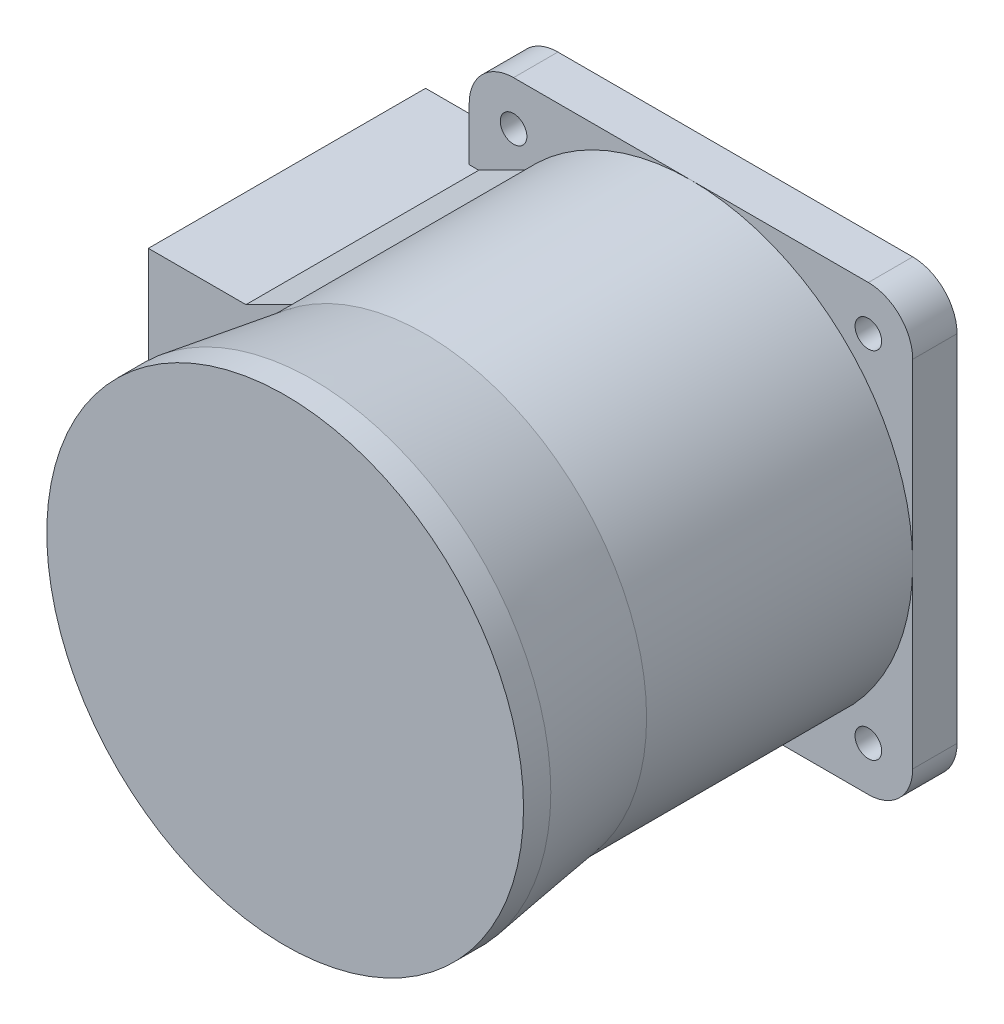
SolidWorks part; units mm, degrees
ref_plane "Piano frontale" through (0, 0, 0) normal (0, 0, 1) x (1, 0, 0)
ref_plane "Piano superiore" through (0, 0, 0) normal (0, 1, 0) x (1, 0, 0)
ref_plane "Piano destro" through (0, 0, 0) normal (1, 0, 0) x (0, 0, -1)
sketch "Schizzo1" plane through (0, 0, 0) normal (0, 0, 1) x (1, 0, 0)
  line L0 (0, 100) -> (0, -100) construction
  line L1 (-80, -100) -> (80, -100)
  line L2 (-100, -80) -> (-100, 80)
  line L3 (-80, 100) -> (80, 100)
  line L4 (100, -80) -> (100, 80)
  line L5 (-100, -100) -> (100, 100) construction
  line L6 (-100, 100) -> (100, -100) construction
  line L7 (-100, 0) -> (100, 0) construction
  arc A0 (80, -100) -> (100, -80) centre (80, -80) ccw
  arc A1 (-80, -100) -> (-100, -80) centre (-80, -80) cw
  arc A2 (80, 100) -> (100, 80) centre (80, 80) cw
  arc A3 (-100, 80) -> (-80, 100) centre (-80, 80) cw
  circle A4 centre (-80, 80) radius 6
  circle A5 centre (-80, -80) radius 6
  circle A6 centre (80, -80) radius 6
  circle A7 centre (80, 80) radius 6
  point P0 (0, 0)
  dimension "D3" = 20
  dimension "D4" = 12
  dimension "D1" = 200
  dimension "D2" = 200
extrude "PiastraBase" add sketch "Schizzo1" along normal blind 20
sketch "Schizzo2" plane through (0, 0, 20) normal (0, 0, 1) x (1, 0, 0)
  circle A0 centre (0, 0) radius 100
  dimension "D1" = 200
extrude "CorpoCilindrico" add sketch "Schizzo2" along normal blind 120
ref_plane "PianoLoft" through (0, 0, 190.7) normal (0, 0, 1) x (1, 0, 0)
sketch "Schizzo3" plane through (0, 0, 190.7) normal (0, 0, 1) x (1, 0, 0)
  circle A0 centre (0, 0) radius 107.5
  circle A1 centre (0, 0) radius 100
  circle A2 centre (0, 0) radius 100 construction
  dimension "D2" = 215
  dimension "D1" = 0
loft "LoftCentrale" add profiles "Schizzo3" section edge at (100, 0, 140) section "Schizzo3"
sketch "Schizzo4" plane through (0, 0, 190.7) normal (0, 0, 1) x (1, 0, 0)
  circle A0 centre (0, 0) radius 107.5 construction
  circle A1 centre (0, 0) radius 107.5
extrude "CorpoCilindricoFinale" add sketch "Schizzo4" along normal blind 12.3
sketch "Schizzo5" plane through (0, 0, 0) normal (0, 0, 1) x (1, 0, 0)
  line L0 (-139.6843, 56) -> (-139.6843, -56)
  line L1 (-139.6843, -56) -> (-95.6843, -56)
  line L2 (-95.6843, -56) -> (-74.6843, -66.5)
  line L3 (-139.6843, 56) -> (-95.6843, 56)
  line L4 (-95.6843, 56) -> (-74.6843, 66.5)
  line L5 (-74.6843, 66.5) -> (-74.6843, -66.5) construction
  arc A2 (-100, 0) -> (0, -100) centre (0, 0) ccw construction
  arc A3 (0, 100) -> (-100, 0) centre (0, 0) ccw construction
  arc A5 (-100, 0) -> (0, -100) centre (0, 0) ccw
  arc A6 (0, 100) -> (-100, 0) centre (0, 0) ccw
  point P6 (-139.6843, 0)
  point P13 (-74.6843, 0)
  dimension "D2" = 65
  dimension "D1" = 21
  dimension "D3" = 112
  dimension "D4" = 133
extrude "PannelloComandi" add sketch "Schizzo5" along normal blind 125
